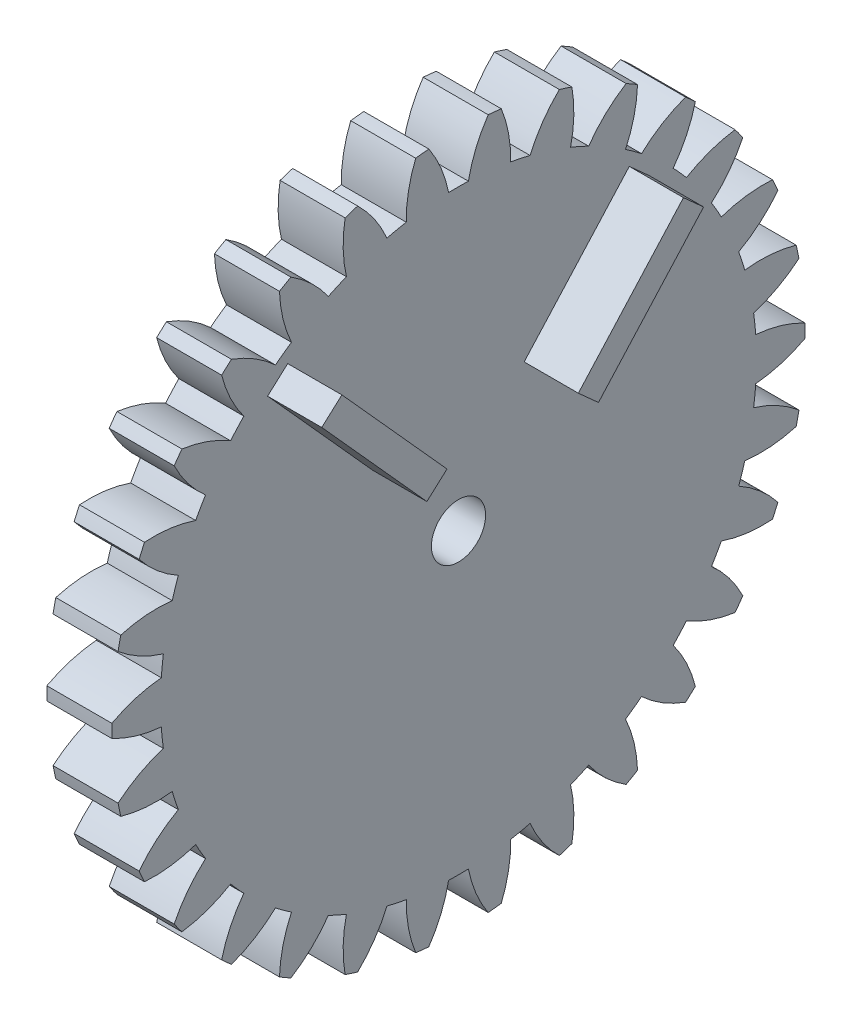
SolidWorks part; units mm, degrees
ref_plane "Plane1" through (0, 0, 0) normal (0, 0, 1) x (1, 0, 0)
ref_plane "Plane2" through (0, 0, 0) normal (0, 1, 0) x (1, 0, 0)
ref_plane "Plane3" through (0, 0, 0) normal (1, 0, 0) x (0, 0, -1)
sketch "HoldingSke" plane through (0, 0, 0) normal (0, 1, 0) x (1, 0, 0)
  line L0 (0, 0) -> (0.2165, -0.125)
  line L1 (-15, 0) -> (100, 0) construction
  line L2 (0, 0) -> (-2.1039, 2.3779)
  line L3 (0, 0) -> (-11.863, 4.5341)
  line L4 (0, 0) -> (7.479, 4.318)
  line L5 (0, 0) -> (-37.4781, -13.9782)
  line L6 (0, 0) -> (-9.9476, -6.7116)
  line L7 (-2.1039, 2.3779) -> (6.5061, 41.4403)
  line L8 (-76.2, 54.61) -> (-74.4, 54.61)
  line L9 (-71.009, 38.7566) -> (-53.1078, 45.2721)
  line L10 (-76.2, 71.12) -> (104.1128, 71.12)
  line L11 (0, 0) -> (-12, 0)
  line L12 (-76.2, 101.6) -> (-76.073, 101.6)
  line L13 (24.9733, 27.94) -> (52.9518, 28.4284)
  line L14 (24.9733, 27.94) -> (24.9743, 27.94)
  line L15 (24.9733, 27.94) -> (100.4006, 29.5858)
  line L16 (-63.627, -4) -> (-12.827, -4)
  circle A0 centre (0, 0) radius 5
  circle A1 centre (0, 0) radius 15
  circle A2 centre (0, 0) radius 15
  circle A3 centre (0, 0) radius 5
  dimension "MHD" = 30
  dimension "Hub_dia" = 30
  dimension "Bore" = 10
  dimension "MBD" = 10
  dimension "Num_teeth" = 30
  dimension "Pitch_radius" = 180.3128
  dimension "Pitch" = 0.25
  dimension "Width" = 12
  dimension "Overall_len" = 40
  dimension "Show_teeth" = 30
  dimension "Thickness" = 12
  dimension "OAL" = 40.0001
  dimension "T_dim" = 1.8
  dimension "Ap" = 20
  dimension "H" = 19.05
  dimension "Backlash" = 0.127
  dimension "Addendum_fac" = 1
  dimension "Dedendum_fac" = 1.25
  dimension "Clearance_fac" = 0.25
  dimension "Dedendum_add" = 0.001
  dimension "Module" = 4
sketch "BasProSke" plane through (0, 0, 0) normal (0, 1, 0) x (1, 0, 0)
  line L0 (-10, 0) -> (60, 0) construction
  line L1 (0, 0) -> (0, 64)
  line L2 (0, 0) -> (12, 0)
  line L3 (12, 0) -> (12, 64)
  line L4 (12, 64) -> (0, 64)
  dimension "Diameter" = 128
  dimension "Thickness" = 12
revolve "Base-Revolve" add sketch "BasProSke" angle 360 about L0
sketch "TooCutSke" plane through (0, 0, 0) normal (1, 0, 0) x (0, 0, -1)
  line L1 (0, 0) -> (0, 107) construction
  line L2 (0, 0) -> (-3.3624, 59.9057) construction
  line L3 (0, 0) -> (-12.5286, 119.2014) construction
  line L4 (-3.3624, 59.9057) -> (-6.2643, 59.6007) construction
  arc A0 (1.8261, 54.9687) -> (-1.8261, 54.9687) centre (0, 0) ccw
  arc A1 (5.4942, 63.7892) -> (-5.4942, 63.7892) centre (0, 0) ccw
  circle A2 centre (0, 0) radius 60 construction
  circle A3 centre (0, 0) radius 56.3816 construction
  arc A4 (-1.8261, 54.9687) -> (-5.4942, 63.7892) centre (-25.377, 50.3477) ccw
  arc A5 (5.4942, 63.7892) -> (1.8261, 54.9687) centre (25.377, 50.3477) ccw
  dimension "Root_dia" = 109.998
  dimension "Overcut_dia" = 128.0508
  dimension "Pitch_dia" = 120
  dimension "Base_dia" = 112.7631
  dimension "Flank_rad" = 24
  dimension "Half_ang" = 6
  dimension "Half_CT" = 2.9179
extrude "ToothCut" cut sketch "TooCutSke" along normal through all
fillet "Breaks" [suppressed] radius 0.08
fillet "RootFillets" [suppressed] radius 1.001
pattern_circular "TeethCuts" count 30 every 12 about axis through (-10, 0, 0) along (1, 0, 0) of "ToothCut", "RootFillets", "Breaks"
sketch "HubNeaOneSke" plane through (0, 0, 0) normal (-1, 0, 0) x (0, 0, 1)
  circle A0 centre (0, 0) radius 15
  dimension "Diameter" = 30
extrude "HubNearOne" add sketch "HubNeaOneSke" along normal blind 28.0001
sketch "HubNeaBotSke" plane through (0, 0, 0) normal (-1, 0, 0) x (0, 0, 1)
  circle A0 centre (0, 0) radius 15
  dimension "Diameter" = 30
extrude "HubNearBoth" [suppressed] add sketch "HubNeaBotSke" along normal blind 14
ref_plane "FarPln" through (12, 0, 0) normal (1, 0, 0) x (0, 0, -1)
sketch "HubFarSke" plane through (12, 0, 0) normal (1, 0, 0) x (0, 0, -1)
  circle A0 centre (0, 0) radius 15
  dimension "Diameter" = 30
extrude "HubFar" [suppressed] add sketch "HubFarSke" along normal blind 14
sketch "BorSke" plane through (0, 0, 0) normal (1, 0, 0) x (0, 0, -1)
  circle A0 centre (0, 0) radius 5
  dimension "Diameter" = 10
extrude "Bore" cut sketch "BorSke" along normal mid plane 80.0001
sketch "KeySke" plane through (0, 0, 0) normal (1, 0, 0) x (0, 0, -1)
  line L0 (-2, 0) -> (-2, 6.8)
  line L1 (-2, 6.8) -> (2, 6.8)
  line L2 (2, 6.8) -> (2, 0)
  line L3 (0, 0) -> (0, 34) construction
  line L4 (-2, 0) -> (2, 0)
  dimension "Offset" = 6.8
  dimension "Width" = 4
extrude "Keyway" [suppressed] cut sketch "KeySke" along normal mid plane 80.0001
pattern_circular "Keyway2" [suppressed] count 2 every 90 about axis through (-10, 0, 0) along (1, 0, 0)
sketch "Sketch1" plane through (12, 0, 0) normal (1, 0, 0) x (0, 0, -1)
  line L0 (0, 54.999) -> (0, -54.999) construction
  line L1 (0, 0) -> (-42.8244, 47.5613) construction
  line L2 (0, 0) -> (42.8244, 47.5613) construction
  line L3 (-35.2416, 39.1397) -> (-31.5259, 42.4854)
  line L4 (-31.5259, 42.4854) -> (-12.1211, 20.9342)
  line L5 (-12.1211, 20.9342) -> (-15.8368, 17.5885)
  line L6 (-15.8368, 17.5885) -> (-35.2416, 39.1397)
  line L7 (15.8368, 17.5885) -> (35.2416, 39.1397)
  line L8 (12.1211, 20.9342) -> (15.8368, 17.5885)
  line L9 (31.5259, 42.4854) -> (12.1211, 20.9342)
  line L10 (35.2416, 39.1397) -> (31.5259, 42.4854)
  arc A0 (1.8261, 54.9687) -> (-1.8261, 54.9687) centre (0, 0) ccw construction
  arc A1 (-1.8261, -54.9687) -> (1.8261, -54.9687) centre (0, 0) ccw construction
  arc A2 (-41.912, 48.3672) -> (-43.7213, 46.7381) centre (0, 0) ccw construction
  dimension "D1" = 29
  dimension "D2" = 5
extrude "Boss-Extrude1" add sketch "Sketch1" along normal blind 10
sketch "Sketch2" plane through (0, 0, 0) normal (0, 0, 1) x (1, 0, 0)
  line L0 (0, 0) -> (-28.0001, 0) construction
  line L1 (0, 15) -> (0, -15) construction
  line L2 (-28.0001, 15) -> (-28.0001, -15) construction
  circle A0 centre (-14, 0) radius 1.5
  dimension "D1" = 3
extrude "Cut-Extrude1" cut sketch "Sketch2" against normal through all and the other way through all
equation "' \"Module@HoldingSke\" = 6.35"
equation "' \"Num_teeth@HoldingSke\" = 12"
equation "' \"Ap@HoldingSke\" =  20"
equation "' \"Width@HoldingSke\" = 0.5 * 25.4"
equation "' \"Hub_dia@HoldingSke\"= 1 * 25.4"
equation "' \"Overall_len@HoldingSke\" = 1.0 * 25.4"
equation "' \"Bore@HoldingSke\" = 0.75 * 25.4"
equation "' \"T_dim@HoldingSke\" = 0.1 * 25.4"
equation "' \"Width@KeySke\" = 0.25 * 25.4"
equation "' \"Show_teeth@HoldingSke\" = 13"
equation "' \"Backlash@HoldingSke\" = 0.009 * 25.4"
equation "' \"Addendum_fac@HoldingSke\" = 1.0"
equation "' \"Dedendum_fac@HoldingSke\" = 1.25"
equation "' \"Dedendum_add@HoldingSke\" = 0.00005 * 25.4"
equation "' \"Clearance_fac@HoldingSke\" = 0.25"
equation "\"Pitch@HoldingSke\" = 1 / \"Module@HoldingSke\""
equation "\"Overcut_dia@TooCutSke\" = (\"Num_teeth@HoldingSke\" + 2 * \"Addendum_fac@HoldingSke\") / \"Pitch@HoldingSke\" + 0.002 * 25.4"
equation "\"Pitch_dia@TooCutSke\" = \"Num_teeth@HoldingSke\" / \"Pitch@HoldingSke\""
equation "\"Base_dia@TooCutSke\" = \"Num_teeth@HoldingSke\" / \"Pitch@HoldingSke\" * cos((\"Ap@HoldingSke\"  * 3.14159265 / 180))"
equation "\"Root_dia@TooCutSke\" = (\"Num_teeth@HoldingSke\" + 2) / \"Pitch@HoldingSke\" - 2 * (\"Addendum_fac@HoldingSke\" + \"Dedendum_fac@HoldingSke\") / \"Pitch@HoldingSke\" - \"Dedendum_add@HoldingSke\" * 2"
equation "\"Half_ang@TooCutSke\" = 180 / \"Num_teeth@HoldingSke\""
equation "\"Half_CT@TooCutSke\" = \"Num_teeth@HoldingSke\" / \"Pitch@HoldingSke\" * sin((3.14159265 / 2 / \"Num_teeth@HoldingSke\")) / 2 - 7 * \"Backlash@HoldingSke\" / 4"
equation "\"Flank_rad@TooCutSke\" = \"Num_teeth@HoldingSke\" / \"Pitch@HoldingSke\" / 5"
equation "\"Radius@RootFillets\" = \"Clearance_fac@HoldingSke\" / \"Pitch@HoldingSke\" + \"Dedendum_add@HoldingSke\""
equation "\"Break_rad@Breaks\" = 0.02 / \"Pitch@HoldingSke\""
equation "\"Thickness@HoldingSke\" = \"Width@HoldingSke\""
equation "\"OAL@HoldingSke\" = \"Thickness@HoldingSke\""
equation "\"MHD@HoldingSke\" = (\"Num_teeth@HoldingSke\" + 2) / \"Pitch@HoldingSke\" - 2 * (\"Addendum_fac@HoldingSke\" + \"Dedendum_fac@HoldingSke\")  / \"Pitch@HoldingSke\" - \"Dedendum_add@HoldingSke\" * 2"
equation "\"MBD@HoldingSke\" = (\"Num_teeth@HoldingSke\" + 2) / \"Pitch@HoldingSke\" - 2 * (\"Addendum_fac@HoldingSke\" + \"Dedendum_fac@HoldingSke\")  / \"Pitch@HoldingSke\" - \"Dedendum_add@HoldingSke\" * 2 - 0.002 * 25.4"
equation "\"MHD@HoldingSke\" = ((sgn( \"MHD@HoldingSke\" - \"Hub_dia@HoldingSke\" )-1)*( \"MHD@HoldingSke\" - \"Hub_dia@HoldingSke\" ))/-2+ \"Hub_dia@HoldingSke\""
equation "\"MBD@HoldingSke\" = ((sgn( \"MBD@HoldingSke\" - \"Bore@HoldingSke\" )-1)*( \"MBD@HoldingSke\" - \"Bore@HoldingSke\" ))/-2+ \"Bore@HoldingSke\""
equation "\"OAL@HoldingSke\" = ((sgn( \"OAL@HoldingSke\" - \"Overall_len@HoldingSke\" )+1)*( \"OAL@HoldingSke\" - \"Overall_len@HoldingSke\" ))/2 + \"Overall_len@HoldingSke\" + 0.000002 * 25.4"
equation "\"Num_teeth@TeethCuts\" = int( \"Show_teeth@HoldingSke\" ) + 1"
equation "\"Num_teeth@TeethCuts\" = ((sgn( \"Num_teeth@TeethCuts\" - \"Num_teeth@HoldingSke\" )-1)*( \"Num_teeth@TeethCuts\" - \"Num_teeth@HoldingSke\" ))/-2+ \"Num_teeth@HoldingSke\""
equation "\"Num_teeth@TeethCuts\" = ((sgn( \"Num_teeth@TeethCuts\" - 2.0)+1)*( \"Num_teeth@TeethCuts\" - 2.0))/2 +2.0"
equation "\"Angle@TeethCuts\" = 360.0 / \"Num_teeth@HoldingSke\""
equation "\"Diameter@BasProSke\" = (\"Num_teeth@HoldingSke\" + 2 * \"Addendum_fac@HoldingSke\") / \"Pitch@HoldingSke\""
equation "\"Thickness@BasProSke\"  = \"Thickness@HoldingSke\""
equation "' \"Fillet_rad@BasProSke\" =  \"Thickness@HoldingSke\" * 0.05"
equation "\"MHD@HoldingSke\" = ((sgn( \"MHD@HoldingSke\" - \"Root_dia@TooCutSke\" )-1)*( \"MHD@HoldingSke\" - \"Root_dia@TooCutSke\" ))/-2+ \"Root_dia@TooCutSke\""
equation "\"Diameter@HubNeaOneSke\" = \"MHD@HoldingSke\""
equation "\"Length@HubNearOne\" = \"OAL@HoldingSke\" - \"Thickness@BasProSke\""
equation "\"Diameter@HubNeaBotSke\" = \"MHD@HoldingSke\""
equation "\"Length@HubNearBoth\" = ( \"OAL@HoldingSke\" - \"Thickness@BasProSke\" ) / 2.0"
equation "\"Thickness@FarPln\" = \"Thickness@BasProSke\""
equation "\"Diameter@HubFarSke\" = \"MHD@HoldingSke\""
equation "\"Length@HubFar\" = ( \"OAL@HoldingSke\" - \"Thickness@BasProSke\" ) / 2.0"
equation "\"Diameter@BorSke\" = \"MBD@HoldingSke\""
equation "\"D1@Bore\" = \"OAL@HoldingSke\" * 2.0"
equation "\"D1@Keyway\" = \"OAL@HoldingSke\" * 2.0"
equation "\"Offset@KeySke\" = \"T_dim@HoldingSke\" + \"MBD@HoldingSke\" / 2.0"
